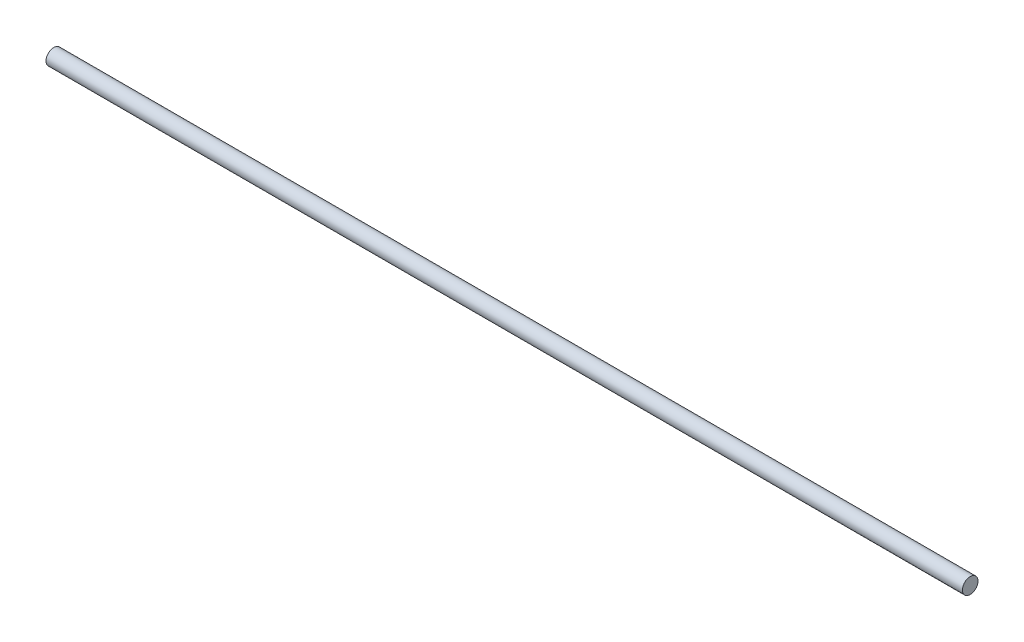
SolidWorks part; units mm, degrees
ref_plane "Front Plane" through (0, 0, 0) normal (0, 0, 1) x (1, 0, 0)
ref_plane "Top Plane" through (0, 0, 0) normal (0, 1, 0) x (1, 0, 0)
ref_plane "Right Plane" through (0, 0, 0) normal (1, 0, 0) x (0, 0, -1)
sketch "Sketch3" plane through (0, 0, 0) normal (1, 0, 0) x (0, 0, -1)
  circle A0 centre (0, 0) radius 4
extrude "Boss-Extrude1" add sketch "Sketch3" along normal blind 470
